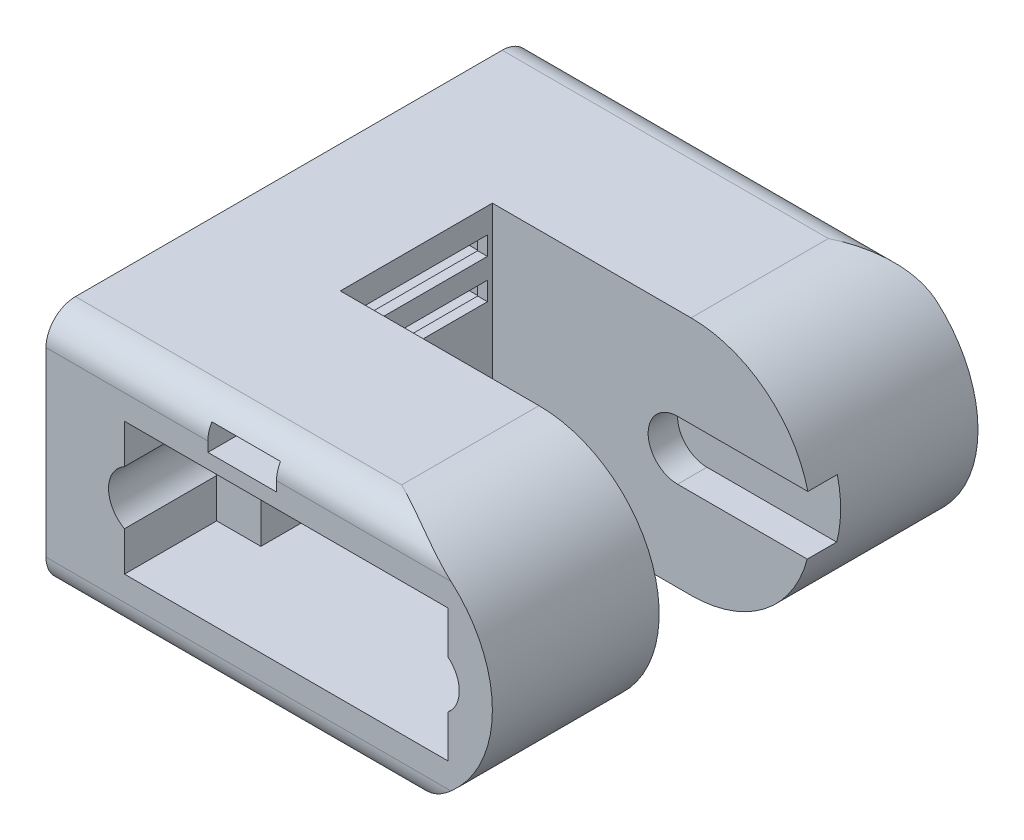
SolidWorks part; units mm, degrees
ref_plane "Спереди" through (0, 0, 0) normal (0, 0, 1) x (1, 0, 0)
ref_plane "Сверху" through (0, 0, 0) normal (0, 1, 0) x (1, 0, 0)
ref_plane "Справа" through (0, 0, 0) normal (1, 0, 0) x (0, 0, -1)
sketch "Эскиз1" plane through (0, 0, 0) normal (1, 0, 0) x (0, 0, -1)
  line L0 (-1050, 0) -> (48950, 0) construction
  line L1 (0, -1021.7777) -> (0, 48978.2223) construction
  line L2 (-24.75, -12.25) -> (24.75, -12.25)
  line L3 (-24.75, -12.25) -> (-24.75, 12.25)
  line L4 (-24.75, 12.25) -> (24.75, 12.25)
  line L5 (24.75, -12.25) -> (24.75, 12.25)
  line L6 (-24.75, -12.25) -> (24.75, 12.25) construction
  line L7 (-24.75, 12.25) -> (24.75, -12.25) construction
  point P3 (0, 0)
  dimension "D1" = 24.5
  dimension "D2" = 49.5
extrude "Бобышка-Вытянуть1" add sketch "Эскиз1" along normal blind 36
sketch "Эскиз2" plane through (0, 0, 0) normal (-1, 0, 0) x (0, 0, 1)
  line L1 (-24.75, -12.25) -> (-24.75, 12.25) construction
  line L2 (24.75, 12.25) -> (24.75, -12.25) construction
  line L3 (24.75, -12.25) -> (-24.75, -12.25) construction
  circle A0 centre (-20, -7.25) radius 2.5
  circle A1 centre (20, -7.25) radius 2.5
  dimension "D3" = 5
  dimension "D1" = 5
  dimension "D2" = 4.75
  dimension "D4" = 4.75
  dimension "D5" = 5
extrude "Вырез-Вытянуть1" cut sketch "Эскиз2" against normal blind 3
sketch "Эскиз3" plane through (0, 0, 0) normal (-1, 0, 0) x (0, 0, 1)
  line L0 (0, -1000) -> (0, 49000) construction
  line L1 (-7.7, 3.4) -> (7.7, 3.4)
  line L2 (-7.7, 7.4) -> (7.7, 7.4)
  line L3 (-7.7, 7.4) -> (-7.7, 10.1)
  line L4 (-7.7, 10.1) -> (7.7, 10.1)
  line L5 (7.7, 7.4) -> (7.7, 10.1)
  line L6 (-7.7, 7.4) -> (7.7, 10.1) construction
  line L7 (-7.7, 10.1) -> (7.7, 7.4) construction
  line L8 (-24.75, 12.25) -> (24.75, 12.25) construction
  line L9 (-7.7, 3.4) -> (-7.7, 6.1)
  line L10 (-7.7, 6.1) -> (7.7, 6.1)
  line L11 (7.7, 3.4) -> (7.7, 6.1)
  line L12 (-7.7, 3.4) -> (7.7, 6.1) construction
  line L13 (-7.7, 6.1) -> (7.7, 3.4) construction
  point P1 (0, 8.75)
  point P11 (0, 4.75)
  dimension "D1" = 15.4
  dimension "D2" = 2.7
  dimension "D3" = 2.15
  dimension "D4" = 2.7
  dimension "D5" = 4
extrude "Вырез-Вытянуть2" cut sketch "Эскиз3" against normal blind 12
sketch "Эскиз9" plane through (0, 12.25, 0) normal (0, -1, 0) x (1, 0, 0)
  line L0 (-1000, 0) -> (49000, 0) construction
  line L6 (36, 24.75) -> (13, 24.75)
  line L7 (36, 24.75) -> (36, -24.75)
  line L8 (36, -24.75) -> (13, -24.75)
  line L10 (13, 24.75) -> (13, -24.75)
  line L11 (0, 24.75) -> (0, -24.75) construction
  dimension "D1" = 13
  dimension "D2" = 24.75
  dimension "D3" = 49.5
extrude "Вырез-Вытянуть9" cut sketch "Эскиз9" along normal blind 24.5
sketch "Эскиз11" plane through (12, 0, 0) normal (-1, 0, 0) x (0, 0, 1)
  line L0 (-1007.6, 8.75) -> (48992.4, 8.75) construction
  line L1 (-7.25, 9.7) -> (7.25, 9.7)
  line L2 (-7.25, 9.7) -> (-7.25, 7.8)
  line L3 (-7.25, 7.8) -> (7.25, 7.8)
  line L4 (7.25, 9.7) -> (7.25, 7.8)
  line L5 (-7.25, 9.7) -> (7.25, 7.8) construction
  line L6 (-7.25, 7.8) -> (7.25, 9.7) construction
  line L7 (-7.7, 10.1) -> (-7.7, 7.4) construction
  line L8 (-1007.6, 4.75) -> (48992.4, 4.75) construction
  line L9 (-7.7, 6.1) -> (-7.7, 3.4) construction
  line L10 (0, -990) -> (0, 49010) construction
  line L11 (7.7, 10.1) -> (-7.7, 10.1) construction
  line L13 (-7.25, 5.7) -> (7.25, 5.7)
  line L14 (-7.25, 5.7) -> (-7.25, 3.8)
  line L15 (-7.25, 3.8) -> (7.25, 3.8)
  line L16 (7.25, 5.7) -> (7.25, 3.8)
  line L17 (-7.25, 5.7) -> (7.25, 3.8) construction
  line L18 (-7.25, 3.8) -> (7.25, 5.7) construction
  point P0 (0, 8.75)
  point P10 (-7.7, 8.75)
  point P15 (-7.7, 4.75)
  point P16 (0, 4.75)
  point P20 (0, 10.1)
  dimension "D1" = 1.9
  dimension "D2" = 14.5
  dimension "D3" = 1.9
extrude "Вырез-Вытянуть8" cut sketch "Эскиз11" against normal blind 2
fillet "Скругление1" radius 3 4 edges at (6.5, 12.25, -24.75) (6.5, -12.25, -24.75) (6.5, 12.25, 24.75) (6.5, -12.25, 24.75)
sketch "Эскиз12" plane through (13, 0, 0) normal (1, 0, 0) x (0, 0, -1)
  line L0 (-7.75, 12.25) -> (-7.75, -12.25)
  line L1 (-21.75, 12.25) -> (21.75, 12.25) construction
  line L2 (-21.75, -12.25) -> (21.75, -12.25) construction
  line L3 (-7.75, -12.25) -> (-21.75, -12.25)
  line L5 (-21.75, 12.25) -> (-7.75, 12.25)
  line L6 (-24.75, -9.25) -> (-24.75, 9.25) construction
  line L7 (-24.75, -9.25) -> (-24.75, 9.25)
  line L8 (21.75, 12.25) -> (7.75, 12.25)
  line L9 (7.75, 12.25) -> (7.75, -12.25)
  line L10 (7.75, -12.25) -> (21.75, -12.25)
  line L11 (24.75, -9.25) -> (24.75, 9.25) construction
  line L12 (24.75, -9.25) -> (24.75, 9.25)
  arc A0 (-24.75, -9.25) -> (-21.75, -12.25) centre (-21.75, -9.25) ccw construction
  arc A1 (-21.75, 12.25) -> (-24.75, 9.25) centre (-21.75, 9.25) ccw construction
  arc A2 (-24.75, -9.25) -> (-21.75, -12.25) centre (-21.75, -9.25) ccw
  arc A3 (-21.75, 12.25) -> (-24.75, 9.25) centre (-21.75, 9.25) ccw
  arc A4 (24.75, 9.25) -> (21.75, 12.25) centre (21.75, 9.25) ccw construction
  arc A5 (21.75, -12.25) -> (24.75, -9.25) centre (21.75, -9.25) ccw construction
  arc A6 (24.75, 9.25) -> (21.75, 12.25) centre (21.75, 9.25) ccw
  arc A7 (21.75, -12.25) -> (24.75, -9.25) centre (21.75, -9.25) ccw
  dimension "D1" = 17
extrude "Бобышка-Вытянуть2" add sketch "Эскиз12" along normal blind 32.5
sketch "Эскиз13" plane through (0, 0, 7.75) normal (0, 0, -1) x (-1, 0, 0)
  line L0 (-1048, 0) -> (48952, 0) construction
  line L1 (-45.5, -12.25) -> (-45.5, 12.25) construction
  line L2 (-24.25, -987.75) -> (-24.25, 49012.25) construction
  line L4 (0, -9.25) -> (0, 9.25) construction
  line L5 (-36, -6.75) -> (-12.5, -6.75)
  line L6 (-36, -6.75) -> (-36, 6.75)
  line L7 (-36, 6.75) -> (-12.5, 6.75)
  line L8 (-12.5, -6.75) -> (-12.5, 6.75)
  line L9 (-36, -6.75) -> (-12.5, 6.75) construction
  line L10 (-36, 6.75) -> (-12.5, -6.75) construction
  point P5 (-45.5, 0)
  point P6 (-24.25, 0)
  dimension "D1" = 23.5
  dimension "D2" = 13.5
  dimension "D3" = 12.5
extrude "Вырез-Вытянуть10" cut sketch "Эскиз13" against normal blind 7.6
sketch "Эскиз14" plane through (0, 0, 15.35) normal (0, 0, -1) x (-1, 0, 0)
  line L0 (-1042.25, 0) -> (48957.75, 0) construction
  line L1 (-36, 6.75) -> (-36, -6.75) construction
  line L2 (-24.5, -993.25) -> (-24.5, 49006.75) construction
  line L3 (-13, 6.75) -> (-36, 6.75) construction
  line L5 (-41, -6.75) -> (-8, -6.75)
  line L6 (-41, -6.75) -> (-41, 6.75)
  line L7 (-41, 6.75) -> (-8, 6.75)
  line L8 (-8, -6.75) -> (-8, 6.75)
  line L9 (-41, -6.75) -> (-8, 6.75) construction
  line L10 (-41, 6.75) -> (-8, -6.75) construction
  point P5 (-36, 0)
  point P6 (-24.5, 0)
  point P10 (-24.5, 6.75)
  dimension "D1" = 33
extrude "Вырез-Вытянуть11" cut sketch "Эскиз14" against normal up to surface (9.4 mm away) up to face at (22.75, 0, 24.75)
sketch "Эскиз16" plane through (0, 0, 24.75) normal (0, 0, 1) x (1, 0, 0)
  line L0 (9.5, -1000.4904) -> (9.5, 48999.5096) construction
  line L1 (39, -999.8452) -> (39, 49000.1548) construction
  line L2 (12.5, -6.75) -> (12.5, 6.75) construction
  line L3 (36, 6.75) -> (36, -6.75) construction
  line L4 (-981.25, 0) -> (49018.75, 0) construction
  circle A0 centre (9.5, 0) radius 1.45
  circle A1 centre (39, 0) radius 1.45
  point P11 (12.5, 0)
  dimension "D3" = 2.9
  dimension "D1" = 3
  dimension "D2" = 3
extrude "Вырез-Вытянуть12" cut sketch "Эскиз16" against normal up to surface (17 mm away) up to face at (26.875, 0, 7.75)
sketch "Эскиз17" plane through (0, 0, 24.75) normal (0, 0, 1) x (1, 0, 0)
  circle A0 centre (9.5, 0) radius 3.125
  circle A1 centre (39, 0) radius 3.125
  dimension "D1" = 6.25
extrude "Вырез-Вытянуть13" cut sketch "Эскиз17" against normal up to surface (9.4 mm away) up to face at (10.95, 0, 15.35)
sketch "Эскиз18" plane through (0, 0, -7.75) normal (0, 0, 1) x (1, 0, 0)
  line L1 (45.5, 9.25) -> (45.5, -9.25) construction
  line L3 (45.5, -12.25) -> (0, -12.25) construction
  line L5 (31.875, 2.875) -> (45.5, 2.875)
  line L7 (31.875, -3.125) -> (45.5, -3.125)
  line L8 (45.5, 2.875) -> (45.5, -3.125)
  arc A0 (31.875, 2.875) -> (31.875, -3.125) centre (31.875, -0.125) ccw
  dimension "D3" = 6
  dimension "D1" = 13.625
  dimension "D2" = 12.125
extrude "Вырез-Вытянуть14" cut sketch "Эскиз18" against normal blind 3
sketch "Эскиз19" plane through (0, 0, -24.75) normal (0, 0, -1) x (-1, 0, 0)
  line L0 (0, 12.25) -> (-45.5, 12.25) construction
  line L1 (-45.5, -12.25) -> (0, -12.25) construction
  line L2 (-33.25, 12.25) -> (-46.5, 12.25)
  line L3 (-46.5, 12.25) -> (-46.5, -12.25)
  line L4 (-46.5, -12.25) -> (-33.25, -12.25)
  line L5 (-45.5, 9.25) -> (-45.5, -9.25) construction
  arc A0 (-33.25, 12.25) -> (-33.25, -12.25) centre (-33.25, 0) ccw
  dimension "D1" = 1
extrude "Вырез-Вытянуть15" cut sketch "Эскиз19" against normal up to surface (49.5 mm away)
sketch "Эскиз20" plane through (0, 0, 24.75) normal (0, 0, 1) x (1, 0, 0)
  line L0 (12.5, -6.75) -> (12.5, 6.75) construction
  line L1 (16.5, 8.25) -> (23.5, 8.25)
  line L2 (16.5, 8.25) -> (16.5, 10.75)
  line L3 (16.5, 10.75) -> (23.5, 10.75)
  line L4 (23.5, 8.25) -> (23.5, 10.75)
  line L5 (41, 6.75) -> (8, 6.75) construction
  dimension "D1" = 4
  dimension "D2" = 7
  dimension "D3" = 2.5
  dimension "D4" = 1.5
extrude "Вырез-Вытянуть16" cut sketch "Эскиз20" against normal blind 19
